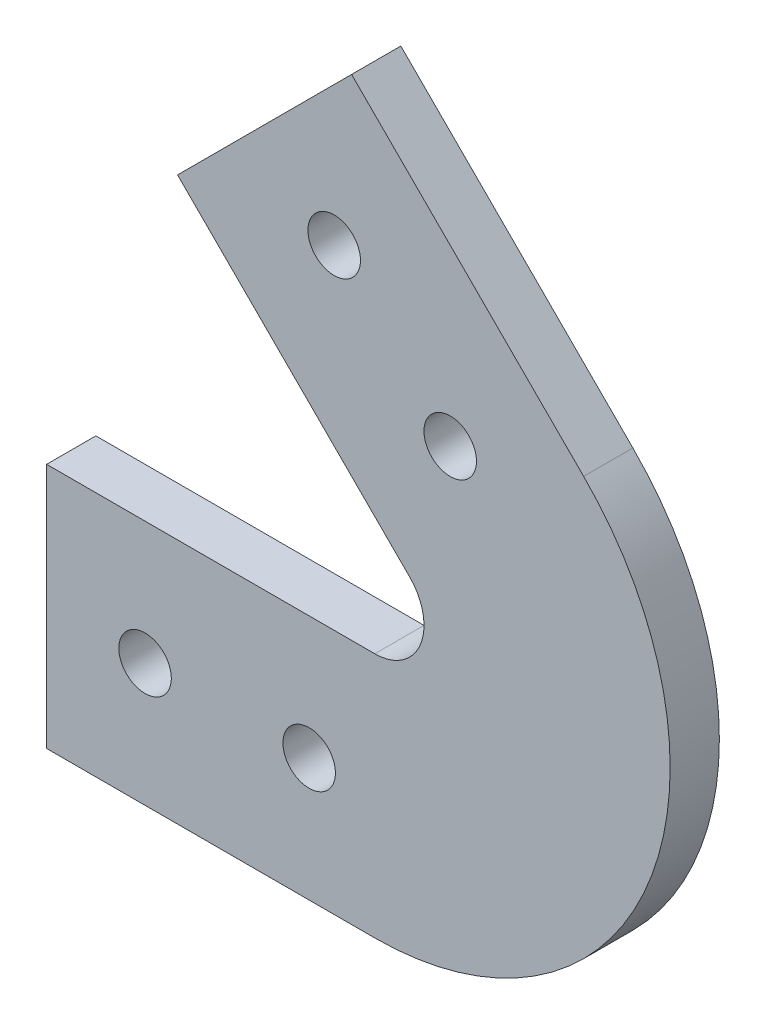
SolidWorks part; units mm, degrees
ref_plane "前视基准面" through (0, 0, 0) normal (0, 0, 1) x (1, 0, 0)
ref_plane "上视基准面" through (0, 0, 0) normal (0, 1, 0) x (1, 0, 0)
ref_plane "右视基准面" through (0, 0, 0) normal (1, 0, 0) x (0, 0, -1)
sketch "草图1" plane through (0, 0, 0) normal (0, 0, 1) x (1, 0, 0)
  line L0 (-23, 187.2397) -> (113, 187.2397) construction
  line L1 (54.1321, 187.2397) -> (74.1321, 187.2397)
  line L2 (54.1321, 187.2397) -> (54.1321, 172.2397)
  line L3 (54.1321, 172.2397) -> (74.1321, 172.2397)
  line L4 (74.1321, 187.2397) -> (74.1321, 172.2397)
  line L5 (38, 172.2397) -> (113, 172.2397) construction
  line L6 (62.1113, 206.5032) -> (72.7179, 217.1098)
  line L7 (62.1113, 206.5032) -> (76.2534, 192.361)
  line L8 (72.7179, 217.1098) -> (86.86, 202.9676)
  line L9 (76.2534, 192.361) -> (86.86, 202.9676)
  line L10 (-29.2132, 297.8277) -> (81.2311, 187.3833) construction
  line L11 (-23, 312.8277) -> (91.8377, 197.9899) construction
  arc A0 (76.2534, 192.361) -> (74.1321, 187.2397) centre (74.1321, 190.2397) cw
  arc A1 (86.86, 202.9676) -> (74.1321, 172.2397) centre (74.1321, 190.2397) cw
  dimension "D3" = 3
  dimension "D1" = 20
  dimension "D2" = 20
extrude "凸台-拉伸1" add sketch "草图1" along normal blind 3 contours L7 L9 L8 L6 | A1 L9 A0 L4 | L4 L1 L2 L3
sketch "草图2" plane through (0, 0, 3) normal (0, 0, 1) x (1, 0, 0)
  line L0 (67.4146, 211.8065) -> (81.6567, 197.5644) construction
  line L1 (62.1113, 206.5032) -> (72.7179, 217.1098) construction
  line L2 (54.1321, 179.7397) -> (72.7278, 179.7397) construction
  line L3 (54.1321, 187.2397) -> (54.1321, 172.2397) construction
  circle A0 centre (71.6572, 207.5638) radius 1.6
  circle A1 centre (78.7283, 200.4928) radius 1.6
  circle A2 centre (60.1321, 179.7397) radius 1.6
  circle A3 centre (70.1321, 179.7397) radius 1.6
  dimension "D1" = 3.2
  dimension "D2" = 6
  dimension "D4" = 10
  dimension "D5" = 6
  dimension "D3" = 10
extrude "切除-拉伸1" cut sketch "草图2" against normal blind 3
